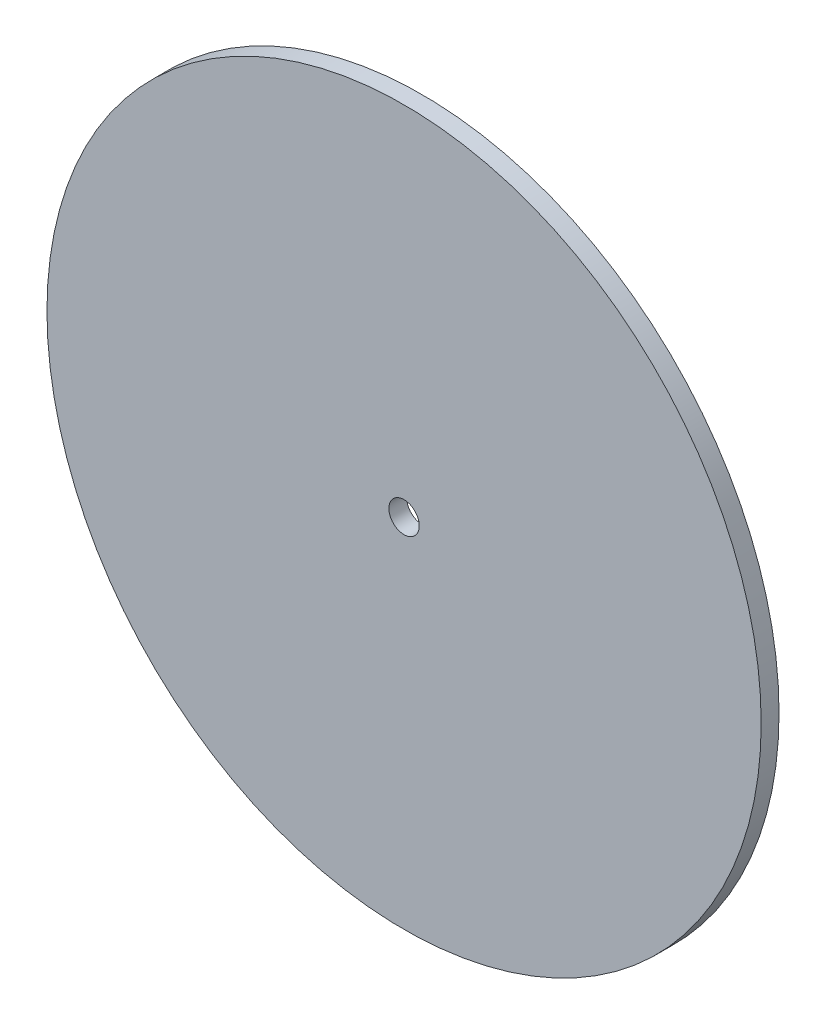
SolidWorks part; units mm, degrees
ref_plane "Front Plane" through (0, 0, 0) normal (0, 0, 1) x (1, 0, 0)
ref_plane "Top Plane" through (0, 0, 0) normal (0, 1, 0) x (1, 0, 0)
ref_plane "Right Plane" through (0, 0, 0) normal (1, 0, 0) x (0, 0, -1)
sketch "Sketch1" plane through (0, 0, 0) normal (0, 0, 1) x (1, 0, 0)
  circle A0 centre (0, 0) radius 20
  circle A1 centre (0, 0) radius 0.85
  dimension "D1" = 40
  dimension "D2" = 1.7
extrude "Boss-Extrude1" add sketch "Sketch1" along normal blind 1
